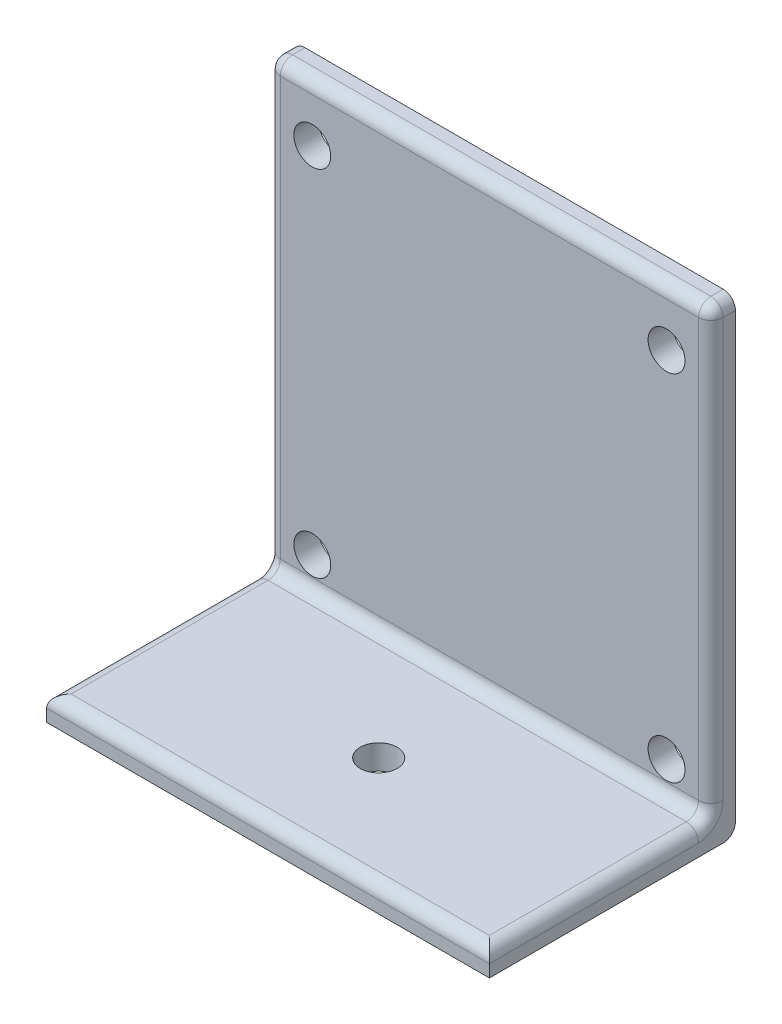
SolidWorks part; units mm, degrees
ref_plane "Front Plane" through (0, 0, 0) normal (0, 0, 1) x (1, 0, 0)
ref_plane "Top Plane" through (0, 0, 0) normal (0, 1, 0) x (1, 0, 0)
ref_plane "Right Plane" through (0, 0, 0) normal (1, 0, 0) x (0, 0, -1)
sketch "Sketch1" plane through (0, 0, 0) normal (0, 1, 0) x (1, 0, 0)
  line L1 (-18, -10) -> (18, -10)
  line L2 (-18, -10) -> (-18, 10)
  line L3 (-18, 10) -> (18, 10)
  line L4 (18, -10) -> (18, 10)
  line L5 (-18, -10) -> (18, 10) construction
  line L6 (-18, 10) -> (18, -10) construction
  point P0 (0, 0)
  dimension "D1" = 20
  dimension "D2" = 36
extrude "Boss-Extrude1" add sketch "Sketch1" along normal blind 2
sketch "Sketch2" plane through (0, 2, 0) normal (0, 1, 0) x (1, 0, 0)
  line L0 (18, -10) -> (18, 10) construction
  line L1 (-18, 10) -> (18, 10)
  line L2 (-18, 10) -> (-18, 8)
  line L3 (-18, 8) -> (18, 8)
  line L4 (18, 10) -> (18, 8)
  dimension "D1" = 2
extrude "Boss-Extrude2" add sketch "Sketch2" along normal blind 36
sketch "Sketch3" plane through (0, 0, -10) normal (0, 0, -1) x (-1, 0, 0)
  line L0 (-18, 38) -> (-18, 0) construction
  line L1 (-14.4, 4.6) -> (14.4, 4.6) construction
  line L2 (-14.4, 4.6) -> (-14.4, 33.4) construction
  line L3 (-14.4, 33.4) -> (14.4, 33.4) construction
  line L4 (14.4, 4.6) -> (14.4, 33.4) construction
  line L5 (-14.4, 4.6) -> (14.4, 33.4) construction
  line L6 (-14.4, 33.4) -> (14.4, 4.6) construction
  line L7 (-18, 38) -> (18, 38) construction
  circle A0 centre (-14.4, 33.4) radius 1.5
  circle A1 centre (14.4, 33.4) radius 1.5
  circle A2 centre (14.4, 4.6) radius 1.5
  circle A3 centre (-14.4, 4.6) radius 1.5
  point P0 (0, 19)
  point P7 (-18, 19)
  point P10 (0, 38)
  point P21 (0, 19)
  dimension "D2" = 3
  dimension "D1" = 28.8
  dimension "D3" = 4
extrude "Cut-Extrude1" cut sketch "Sketch3" against normal up to next
sketch "Sketch4" plane through (0, 2, 0) normal (0, 1, 0) x (1, 0, 0)
  line L4 (18, 8) -> (-18, 8)
  line L5 (-18, 8) -> (-18, -10)
  line L6 (-18, -10) -> (18, -10)
  line L7 (18, -10) -> (18, 8)
  line L8 (18, 8) -> (-18, 8)
  line L9 (-18, 8) -> (-18, -10)
  line L10 (-18, -10) -> (18, -10)
  line L11 (18, -10) -> (18, 8)
  circle A0 centre (0, -1) radius 1.5
  point P6 (-18, -1)
  point P7 (0, -10)
  dimension "D2" = 3
  dimension "D1" = 0
extrude "Cut-Extrude3" cut sketch "Sketch4" against normal up to next contours A0
fillet "Fillet1" radius 1 10 edges at (-18, 2, 1) (18, 2, 1) (0, 2, 10) (0, 2, -8) (18, 20, -8) (0, 38, -8) (-18, 20, -8) (0, 0, -10) (18, 38, -9) (-18, 38, -9)
